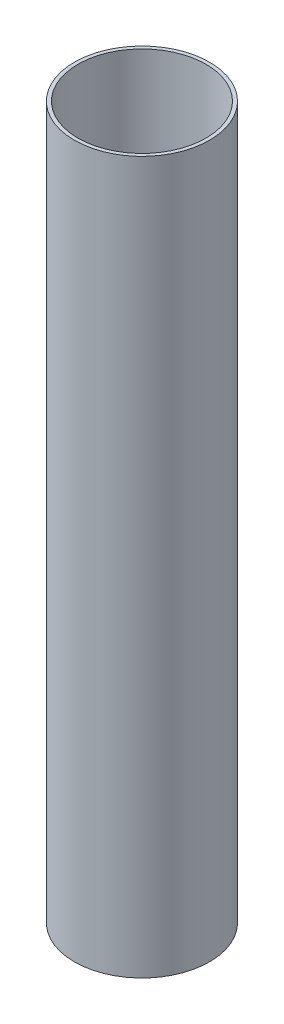
SolidWorks part; units mm, degrees
material "Hexcel AS4C (3000 Filaments)"
ref_plane "Front Plane" through (0, 0, 0) normal (0, 0, 1) x (1, 0, 0)
ref_plane "Top Plane" through (0, 0, 0) normal (0, 1, 0) x (1, 0, 0)
ref_plane "Right Plane" through (0, 0, 0) normal (1, 0, 0) x (0, 0, -1)
sketch "Sketch1" plane through (0, 0, 0) normal (0, 1, 0) x (1, 0, 0)
  circle A0 centre (0, 0) radius 19
  circle A1 centre (0, 0) radius 18
  dimension "D1" = 38
  dimension "D2" = 1
extrude "Boss-Extrude1" add sketch "Sketch1" along normal blind 200
